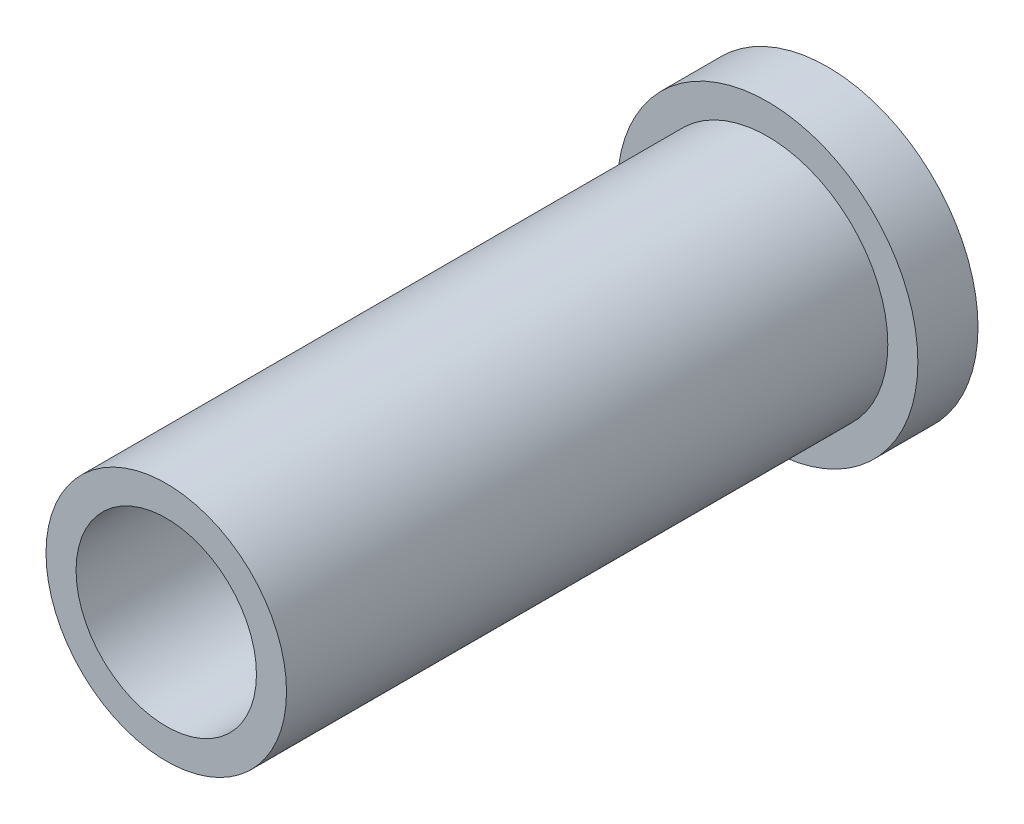
SolidWorks part; units mm, degrees
ref_plane "Plano frontal" through (0, 0, 0) normal (0, 0, 1) x (1, 0, 0)
ref_plane "Plano superior" through (0, 0, 0) normal (0, 1, 0) x (1, 0, 0)
ref_plane "Plano direito" through (0, 0, 0) normal (1, 0, 0) x (0, 0, -1)
sketch "Esboço1" plane through (0, 0, 0) normal (0, 0, 1) x (1, 0, 0)
  circle A0 centre (0, 0) radius 7.5
  dimension "D1" = 15
extrude "Ressalto-extrusão1" add sketch "Esboço1" along normal blind 3
sketch "Esboço2" plane through (0, 0, 3) normal (0, 0, 1) x (1, 0, 0)
  circle A0 centre (0, 0) radius 6
  circle A1 centre (0, 0) radius 4.5
  dimension "D1" = 12
  dimension "D2" = 9
extrude "Ressalto-extrusão2" add sketch "Esboço2" along normal blind 30
